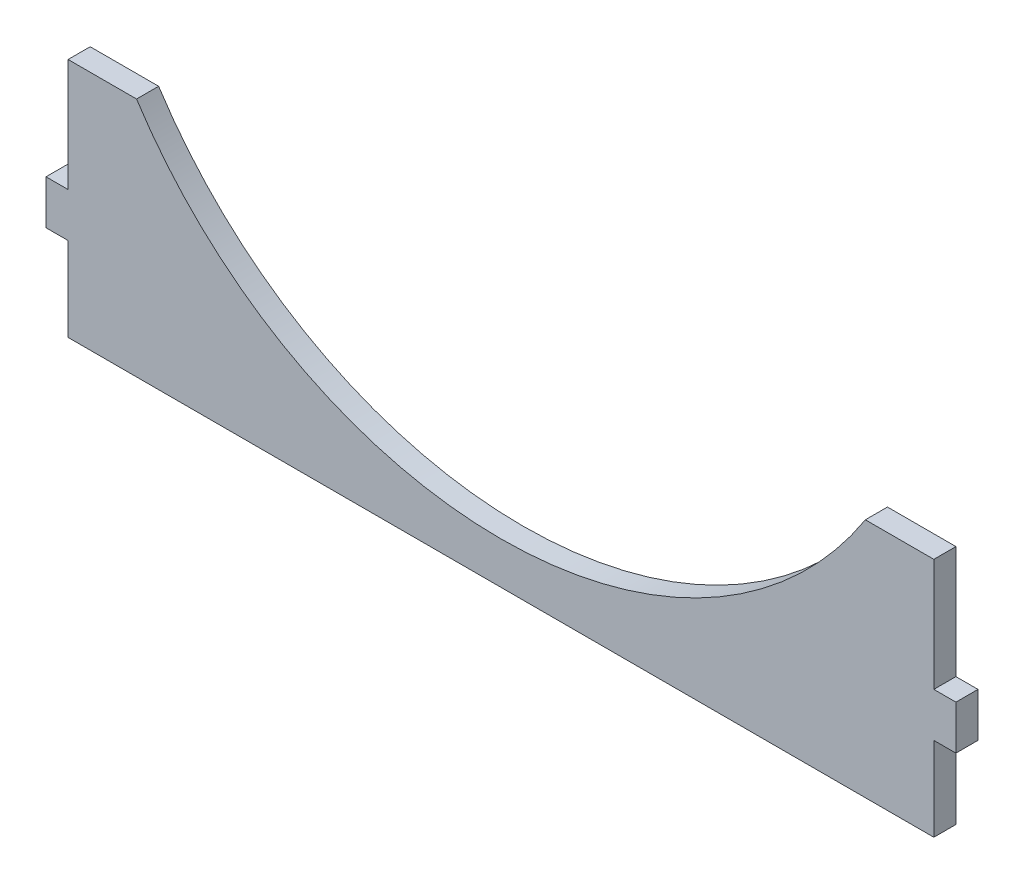
SolidWorks part; units mm, degrees
ref_plane "Plan de face" through (0, 0, 0) normal (0, 0, 1) x (1, 0, 0)
ref_plane "Plan de dessus" through (0, 0, 0) normal (0, 1, 0) x (1, 0, 0)
ref_plane "Plan de droite" through (0, 0, 0) normal (1, 0, 0) x (0, 0, -1)
sketch "Esquisse1" plane through (0, 0, 0) normal (0, 0, 1) x (1, 0, 0)
  line L0 (0, 0) -> (-15.5, 0)
  line L1 (-15.5, 0) -> (-15.5, -25.5)
  line L2 (-15.5, -25.5) -> (-20.5, -25.5)
  line L3 (-20.5, -25.5) -> (-20.5, -35.5)
  line L4 (-20.5, -35.5) -> (-15.5, -35.5)
  line L5 (-15.5, -35.5) -> (-15.5, -54.5)
  line L6 (-15.5, -54.5) -> (180.5, -54.5)
  line L7 (180.5, -54.5) -> (180.5, -35.5)
  line L8 (180.5, -35.5) -> (185.5, -35.5)
  line L9 (185.5, -35.5) -> (185.5, -25.5)
  line L10 (185.5, -25.5) -> (180.5, -25.5)
  line L11 (180.5, -25.5) -> (180.5, 0)
  line L12 (180.5, 0) -> (165, 0)
  arc A0 (165, 0) -> (0, 0) centre (82.5, 53.125) cw
  point P17 (82.5, -45)
extrude "Boss.-Extru.1" add sketch "Esquisse1" along normal blind 5
